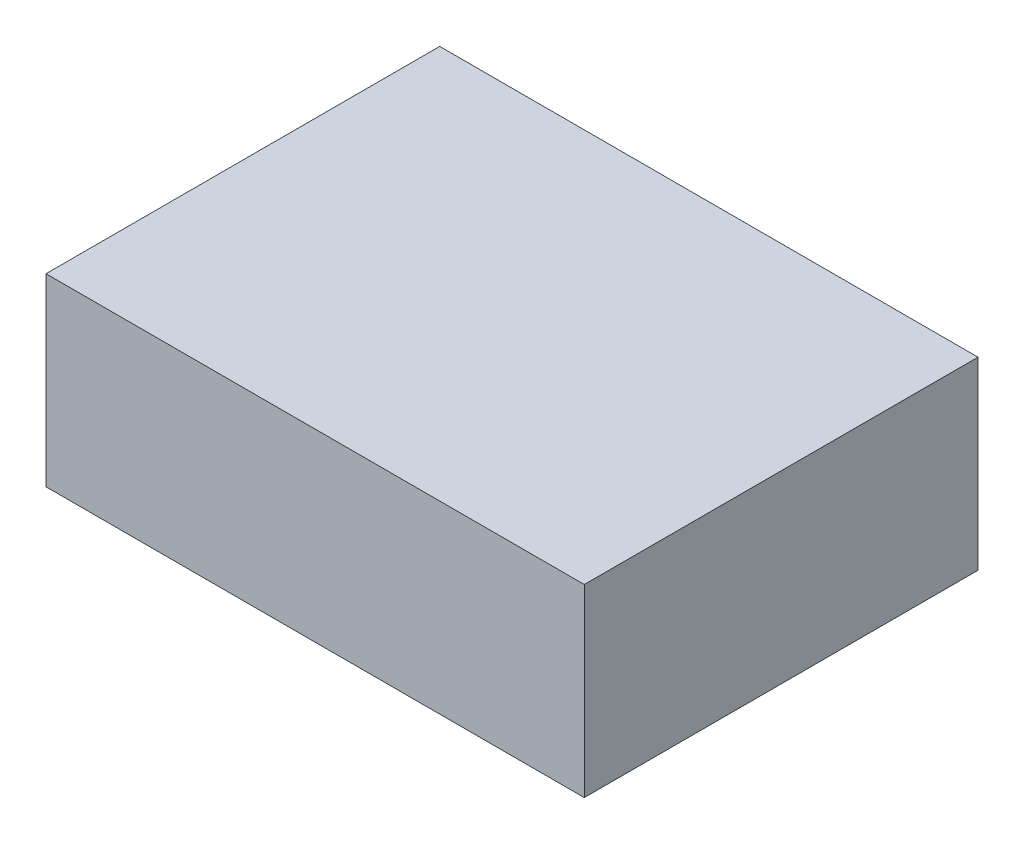
SolidWorks part; units mm, degrees
ref_plane "Front Plane" through (0, 0, 0) normal (0, 0, 1) x (1, 0, 0)
ref_plane "Top Plane" through (0, 0, 0) normal (0, 1, 0) x (1, 0, 0)
ref_plane "Right Plane" through (0, 0, 0) normal (1, 0, 0) x (0, 0, -1)
sketch "Sketch1" plane through (0, 0, 0) normal (0, 1, 0) x (1, 0, 0)
  line L1 (-87.5, 64) -> (87.5, 64)
  line L2 (-87.5, 64) -> (-87.5, -64)
  line L3 (-87.5, -64) -> (87.5, -64)
  line L4 (87.5, 64) -> (87.5, -64)
  line L5 (-87.5, 64) -> (87.5, -64) construction
  line L6 (-87.5, -64) -> (87.5, 64) construction
  point P0 (0, 0)
  dimension "D1" = 175
  dimension "D2" = 128
extrude "Boss-Extrude1" add sketch "Sketch1" along normal blind 60
